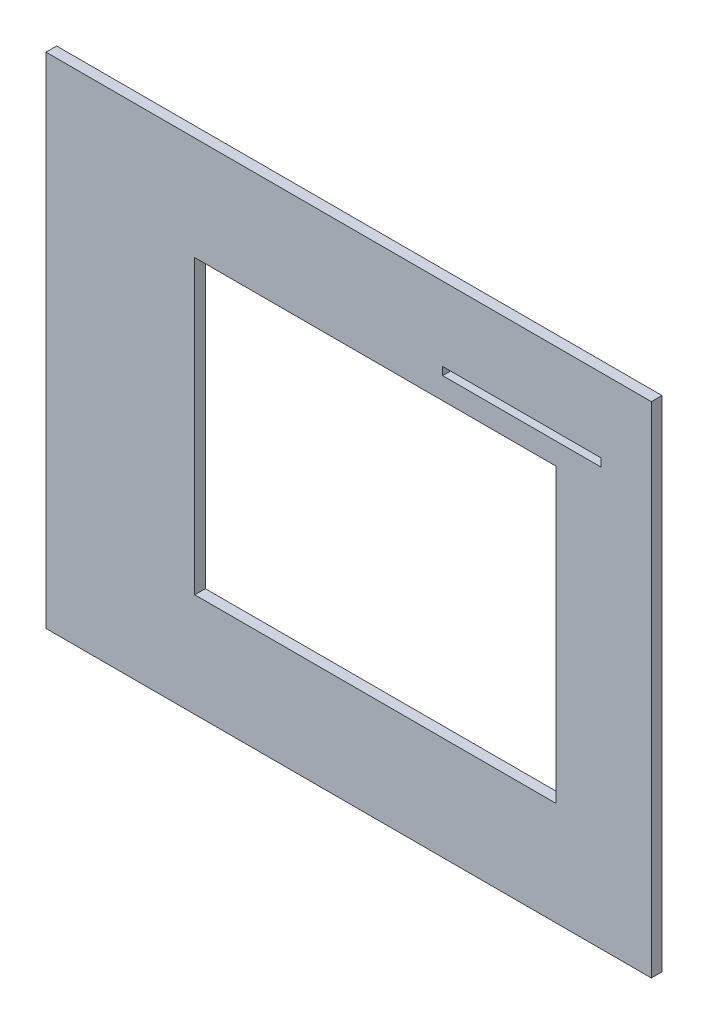
SolidWorks part; units mm, degrees
ref_plane "Front Plane" through (0, 0, 0) normal (0, 0, 1) x (1, 0, 0)
ref_plane "Top Plane" through (0, 0, 0) normal (0, 1, 0) x (1, 0, 0)
ref_plane "Right Plane" through (0, 0, 0) normal (1, 0, 0) x (0, 0, -1)
sketch "Sketch1" plane through (0, 0, 0) normal (0, 0, 1) x (1, 0, 0)
  line L0 (86.0378, 59.651) -> (-27.9622, -34.349) construction
  line L1 (-27.9622, 59.651) -> (86.0378, 59.651)
  line L2 (-27.9622, 59.651) -> (-27.9622, -34.349)
  line L3 (-27.9622, -34.349) -> (86.0378, -34.349)
  line L4 (86.0378, 59.651) -> (86.0378, -34.349)
  line L5 (-27.9622, 59.651) -> (86.0378, -34.349) construction
  line L6 (-27.9622, 12.651) -> (86.0378, 12.651) construction
  line L12 (0.0378, -14.849) -> (68.0378, -14.849)
  line L13 (0.0378, -14.849) -> (0.0378, 40.151)
  line L14 (0.0378, 40.151) -> (68.0378, 40.151)
  line L15 (68.0378, -14.849) -> (68.0378, 40.151)
  line L16 (0.0378, -14.849) -> (68.0378, 40.151) construction
  line L17 (0.0378, 40.151) -> (68.0378, -14.849) construction
  point P4 (29.0378, 12.651)
  point P5 (40.1968, 12.651)
  point P8 (29.0378, 12.651)
  point P9 (34.0378, 12.651)
  dimension "D1" = 114
  dimension "D2" = 94
  dimension "D3" = 68
  dimension "D4" = 55
  dimension "D5" = 5
extrude "Boss-Extrude1" add sketch "Sketch1" along normal blind 2
sketch "Sketch2" plane through (0, 0, 0) normal (0, 0, -1) x (-1, 0, 0)
  line L0 (-86.0378, 59.651) -> (27.9622, -34.349) construction
  line L1 (27.9622, 59.651) -> (-86.0378, -34.349) construction
  line L7 (-65.6551, -17.5422) -> (7.5635, 42.831) construction
  line L8 (-67.0796, 41.1854) -> (8.9174, -15.8185) construction
  line L9 (-86.0378, 12.651) -> (27.9622, 12.651) construction
  line L14 (-68.938, -20.2491) -> (10.8464, 45.538) construction
  line L15 (-70.4872, 43.7411) -> (12.325, -18.3742) construction
  line L16 (27.9622, 59.651) -> (27.9622, -34.349) construction
  line L17 (-0.0378, 40.151) -> (-0.0378, -14.849) construction
  line L22 (-0.0378, -14.849) -> (-68.0378, -14.849) construction
  line L23 (-68.0378, -14.849) -> (-68.0378, 40.151) construction
  line L24 (-68.0378, 40.151) -> (-0.0378, 40.151) construction
  line L25 (-0.0378, 40.151) -> (-0.0378, -14.849) construction
  line L26 (-0.0378, -14.849) -> (-68.0378, -14.849) construction
  line L27 (-68.0378, -14.849) -> (-68.0378, 40.151) construction
  line L28 (-68.0378, 40.151) -> (-0.0378, 40.151) construction
  line L29 (-68.0378, 40.151) -> (-0.0378, -14.849) construction
  line L30 (-0.0378, 40.151) -> (-68.0378, -14.849) construction
  line L32 (10.7122, -25.349) -> (-78.7878, -25.349)
  line L33 (10.7122, -25.349) -> (10.7122, 50.651)
  line L34 (10.7122, 50.651) -> (-78.7878, 50.651)
  line L35 (-78.7878, -25.349) -> (-78.7878, 50.651)
  line L36 (10.7122, -25.349) -> (-78.7878, 50.651) construction
  line L37 (10.7122, 50.651) -> (-78.7878, -25.349) construction
  point P8 (-29.0378, 12.651)
  point P15 (-29.0378, 12.651)
  point P23 (-29.0378, 12.651)
  point P24 (-34.0378, 12.651)
  point P26 (-34.0378, 12.651)
  dimension "D1" = 89.5
  dimension "D2" = 76
sketch "Sketch3" plane through (0, 0, 2) normal (0, 0, 1) x (1, 0, 0)
  line L0 (76.5976, 44.9864) -> (46.7227, 44.9864)
  point P2 (74.056, 42.0949)
  point P3 (76.5976, 45.0326)
  point P4 (46.7227, 44.9864)
extrude "Cut-Extrude-Thin1" cut sketch "Sketch3" against normal through all and the other way through all thin thin type mid plane wall 1.5
extrude "Extrude-Thin3" add sketch "Sketch2" along normal blind 2 thin thin type mid plane wall 1
sketch "Sketch4" plane through (0, 0, 0) normal (0, 0, -1) x (-1, 0, 0)
  text T0 "THIS SIDE FACING CAMERA" font "Century Gothic" height 3.175
